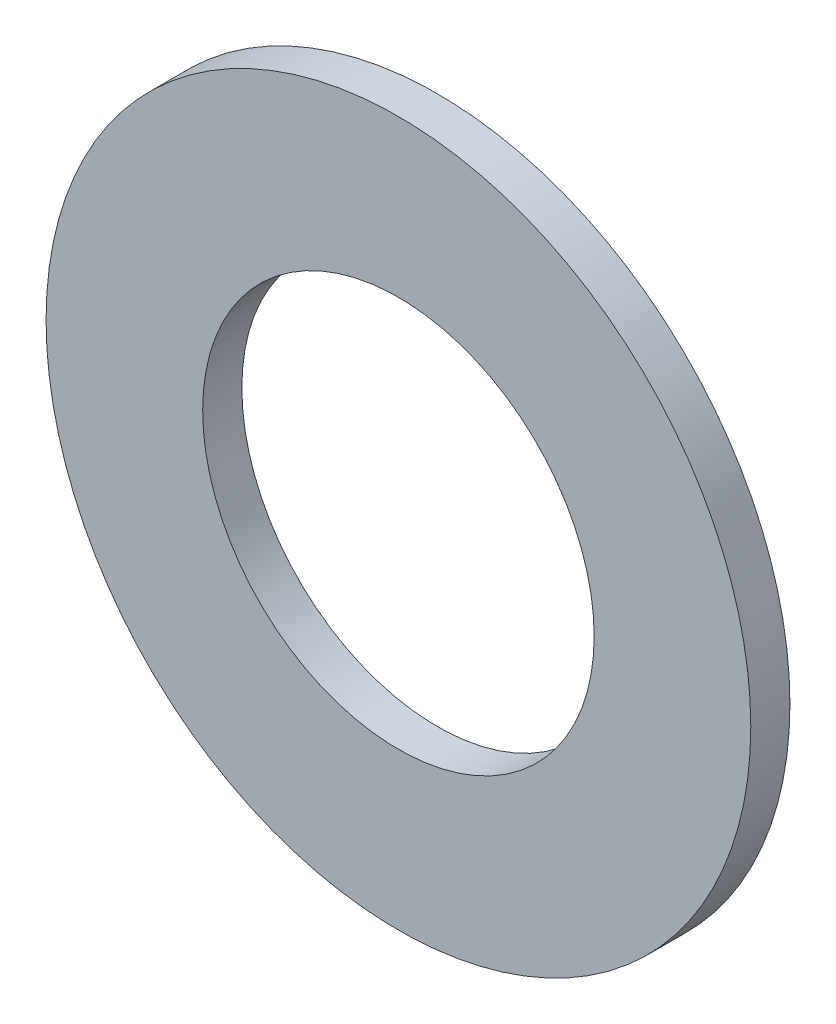
SolidWorks part; units mm, degrees
ref_plane "Front Plane" through (0, 0, 0) normal (0, 0, 1) x (1, 0, 0)
ref_plane "Top Plane" through (0, 0, 0) normal (0, 1, 0) x (1, 0, 0)
ref_plane "Right Plane" through (0, 0, 0) normal (1, 0, 0) x (0, 0, -1)
sketch "Sketch1" plane through (0, 0, 0) normal (0, 0, 1) x (1, 0, 0)
  line L0 (-28.575, 0) -> (28.575, 0) construction
  line L1 (0, -28.575) -> (0, 28.575) construction
  circle A0 centre (0, 0) radius 28.575
  circle A1 centre (0, 0) radius 15.875
  point P4 (0, 0)
  point P9 (0, 0)
  point P10 (15.875, 0)
  dimension "D1" = 31.75
  dimension "OD" = 57.15
  dimension "Wall Thickness" = 12.7
sketch "Sketch2" plane through (0, 0, 0) normal (1, 0, 0) x (0, 0, -1)
  line L0 (76.2, 28.575) -> (-76.2, 28.575) construction
  line L1 (0, 28.575) -> (0, -28.575) construction
  point P3 (-47.625, 28.575)
  point P4 (0, 28.575)
  point P5 (47.625, 28.575)
  dimension "D1" = 28.575
  dimension "D2" = 28.575
  dimension "Length" = 152.4
sketch "Sketch3" plane through (0, 0, 0) normal (0, 0, 1) x (1, 0, 0)
  line L0 (0, -28.575) -> (0, 28.575) construction
  circle A0 centre (0, 0) radius 28.575
  circle A1 centre (0, 0) radius 15.875
  circle A2 centre (0, 0) radius 15.875 construction
extrude "Boss-Extrude1" add sketch "Sketch3" along normal mid plane 152.4
sketch "Sketch4" plane through (0, 0, -76.2) normal (0, 0, -1) x (-1, 0, 0)
  circle A0 centre (0, 0) radius 34.895
extrude "Cut-Extrude1" cut sketch "Sketch4" against normal offset from surface 3.175 and the other way through all up to face at (28.575, 0, 76.2)
equation "\"D1@Boss-Extrude1\" = \"Length@Sketch2\""
equation "\"D1@Sketch2\"=\"OD@Sketch1\"*.5"
equation "\"D2@Sketch2\"=\"D1@Sketch2\""
